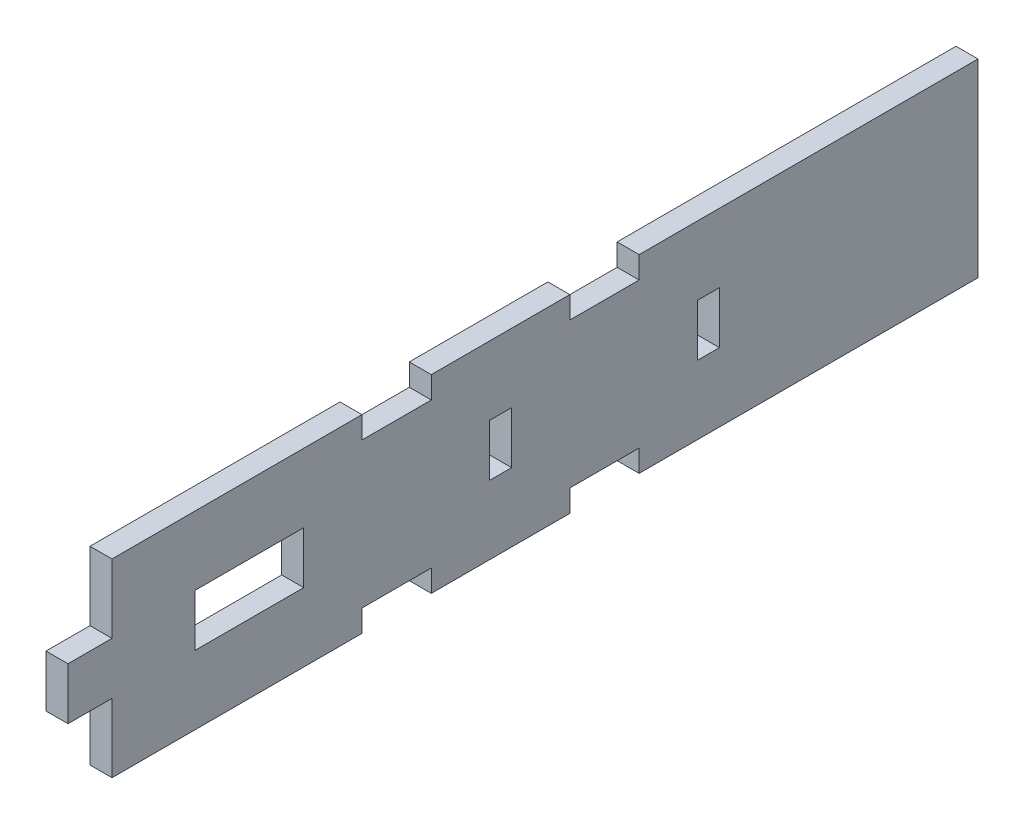
SolidWorks part; units mm, degrees
ref_plane "Front Plane" through (0, 0, 0) normal (0, 0, 1) x (1, 0, 0)
ref_plane "Top Plane" through (0, 0, 0) normal (0, 1, 0) x (1, 0, 0)
ref_plane "Right Plane" through (0, 0, 0) normal (1, 0, 0) x (0, 0, -1)
sketch "Sketch1" plane through (0, 0, 0) normal (1, 0, 0) x (0, 0, -1)
  line L1 (125, -27.35) -> (-125, -27.35)
  line L2 (125, -27.35) -> (125, 27.35)
  line L3 (125, 27.35) -> (-125, 27.35)
  line L4 (-125, -27.35) -> (-125, 27.35)
  line L5 (125, -27.35) -> (-125, 27.35) construction
  line L6 (125, 27.35) -> (-125, -27.35) construction
  line L7 (-125, -7.5) -> (-137.7, -7.5)
  line L8 (-125, -7.5) -> (-125, 7.5)
  line L9 (-125, 7.5) -> (-137.7, 7.5)
  line L10 (-137.7, -7.5) -> (-137.7, 7.5)
  line L11 (-125, -7.5) -> (-137.7, 7.5) construction
  line L12 (-125, 7.5) -> (-137.7, -7.5) construction
  point P0 (0, 0)
  point P6 (-131.35, 0)
  dimension "D1" = 12.7
  dimension "D2" = 15
  dimension "D3" = 250
  dimension "D4" = 54.7
extrude "Boss-Extrude1" add sketch "Sketch1" along normal blind 6.35
sketch "Sketch2" plane through (6.35, 0, 0) normal (1, 0, 0) x (0, 0, -1)
  line L0 (-125, 7.5) -> (-125, 27.35) construction
  line L1 (-69.65, -7.5) -> (-76, -7.5)
  line L2 (-69.65, -7.5) -> (-69.65, 7.5)
  line L3 (-69.65, 7.5) -> (-76, 7.5)
  line L4 (-76, -7.5) -> (-76, 7.5)
  line L5 (-69.65, -7.5) -> (-76, 7.5) construction
  line L6 (-69.65, 7.5) -> (-76, -7.5) construction
  point P0 (-72.825, 0)
  point P7 (-125, 17.425)
  dimension "D1" = 49
  dimension "D2" = 6.35
  dimension "D3" = 15
extrude "Cut-Extrude1" cut sketch "Sketch2" against normal through all
pattern_linear "LPattern1" count 3 spacing 60 along (0, 0, -1) of "Cut-Extrude1"
sketch "Sketch3" plane through (6.35, 0, 0) normal (1, 0, 0) x (0, 0, -1)
  line L0 (-69.65, 7.5) -> (-76, 7.5) construction
  line L1 (-76, -7.5) -> (-101, -7.5)
  line L2 (-76, -7.5) -> (-76, 7.5)
  line L3 (-76, 7.5) -> (-101, 7.5)
  line L4 (-101, -7.5) -> (-101, 7.5)
  point P5 (-101, -7.5)
  dimension "D1" = 25
extrude "Cut-Extrude2" cut sketch "Sketch3" against normal through all
sketch "Sketch4" plane through (6.35, 0, 0) normal (1, 0, 0) x (0, 0, -1)
  line L0 (-69.65, -7.5) -> (-16, -7.5) construction
  line L1 (-9.65, -7.5) -> (44, -7.5) construction
  line L3 (-32.825, 21) -> (-52.825, 21)
  line L4 (-32.825, 21) -> (-32.825, 27.35)
  line L5 (-32.825, 27.35) -> (-52.825, 27.35)
  line L6 (-52.825, 21) -> (-52.825, 27.35)
  line L7 (-32.825, 21) -> (-52.825, 27.35) construction
  line L8 (-32.825, 27.35) -> (-52.825, 21) construction
  line L9 (27.175, 21) -> (7.175, 21)
  line L10 (27.175, 21) -> (27.175, 27.35)
  line L11 (27.175, 27.35) -> (7.175, 27.35)
  line L12 (7.175, 21) -> (7.175, 27.35)
  line L13 (27.175, 21) -> (7.175, 27.35) construction
  line L14 (27.175, 27.35) -> (7.175, 21) construction
  line L16 (125, 27.35) -> (-125, 27.35) construction
  point P8 (-42.825, 24.175)
  point P13 (17.175, 24.175)
  point P18 (0, 0)
  point P19 (-42.825, -7.5)
  point P20 (0, 0)
  point P21 (17.175, -7.5)
  dimension "D1" = 6.35
  dimension "D2" = 20
extrude "Cut-Extrude3" cut sketch "Sketch4" against normal through all
mirror "Mirror1" about plane through (0, 0, 0) normal (0, 1, 0) of "Cut-Extrude3"
